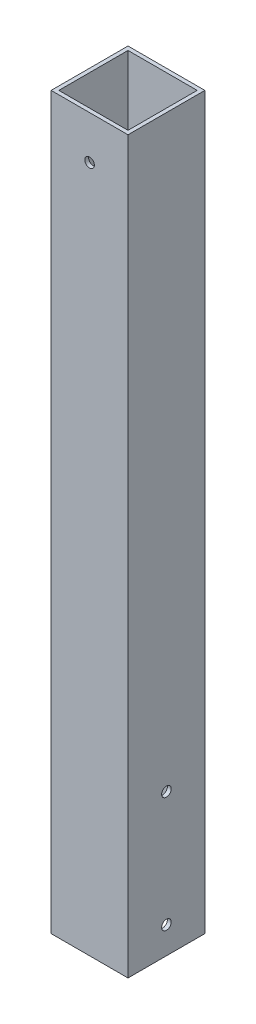
SolidWorks part; units mm, degrees
ref_plane "Ön Düzlem" through (0, 0, 0) normal (0, 0, 1) x (1, 0, 0)
ref_plane "Üst Düzlem" through (0, 0, 0) normal (0, 1, 0) x (1, 0, 0)
ref_plane "Sağ Düzlem" through (0, 0, 0) normal (1, 0, 0) x (0, 0, -1)
sketch "Sketch1" plane through (0, 0, 0) normal (0, 1, 0) x (1, 0, 0)
  line L1 (0, 0) -> (-40, 0)
  line L2 (0, 0) -> (0, 40)
  line L3 (0, 40) -> (-40, 40)
  line L4 (-40, 0) -> (-40, 40)
  dimension "D1" = 40
extrude "Extrude-Thin1" add sketch "Sketch1" along normal blind 380 thin
sketch "Sketch2" plane through (0, 0, 0) normal (0, 0, 1) x (1, 0, 0)
  line L0 (-40, 380) -> (0, 380) construction
  line L1 (-40, 380) -> (-40, 0) construction
  circle A0 centre (-20, 357.5) radius 2.5
  dimension "D1" = 5
  dimension "D2" = 22.5
  dimension "D3" = 20
extrude "Cut-Extrude1" cut sketch "Sketch2" against normal blind 50
sketch "Sketch3" plane through (-40, 0, 0) normal (-1, 0, 0) x (0, 0, 1)
  line L0 (-40, 380) -> (-40, 0) construction
  line L1 (-40, 0) -> (0, 0) construction
  circle A0 centre (-20, 14) radius 2.5
  circle A1 centre (-20, 74) radius 2.5
  point P6 (0, 0)
  dimension "D1" = 5
  dimension "D2" = 5
  dimension "D3" = 60
  dimension "D4" = 20
  dimension "D5" = 14
extrude "Cut-Extrude2" cut sketch "Sketch3" against normal blind 50
